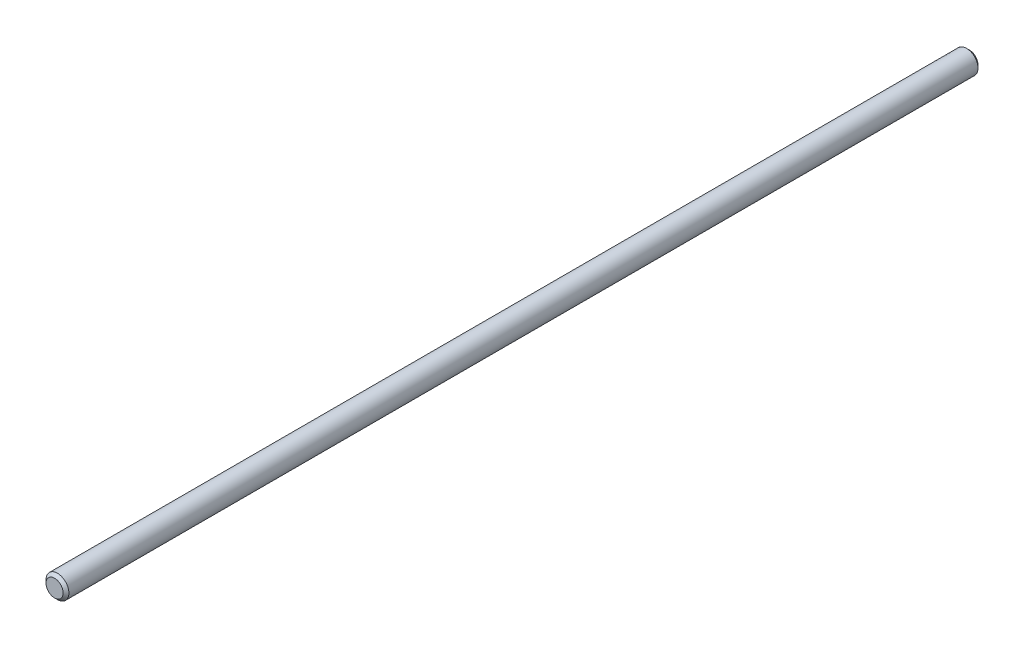
SolidWorks part; units mm, degrees
material "AISI 4340 Steel, annealed"
ref_plane "Front Plane" through (0, 0, 0) normal (0, 0, 1) x (1, 0, 0)
ref_plane "Top Plane" through (0, 0, 0) normal (0, 1, 0) x (1, 0, 0)
ref_plane "Right Plane" through (0, 0, 0) normal (1, 0, 0) x (0, 0, -1)
sketch "Sketch2" plane through (0, 0, 0) normal (0, 0, 1) x (1, 0, 0)
  circle A0 centre (0, 0) radius 2
  dimension "D1" = 4
extrude "Boss-Extrude1" add sketch "Sketch2" along normal mid plane 160
chamfer "Chamfer1" distance 0.5 angle 45 2 edges at (2, 0, -80) (2, 0, 80)
cosmetic thread "Cosmetic Thread1"
cosmetic thread "Cosmetic Thread2"
cosmetic thread "Cosmetic Thread3"
